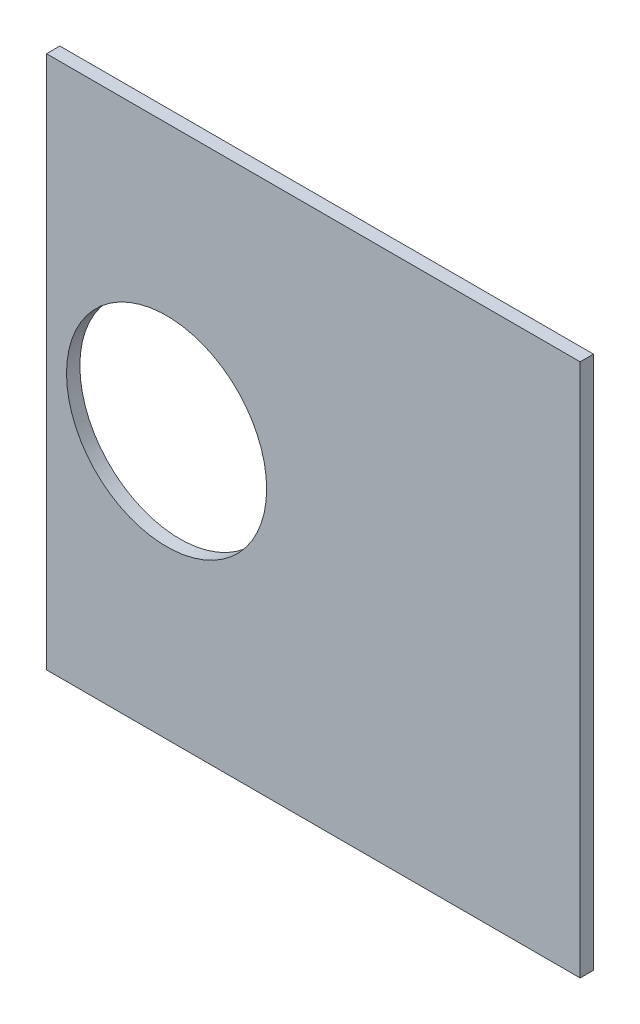
SolidWorks part; units mm, degrees
ref_plane "前视基准面" through (0, 0, 0) normal (0, 0, 1) x (1, 0, 0)
ref_plane "上视基准面" through (0, 0, 0) normal (0, 1, 0) x (1, 0, 0)
ref_plane "右视基准面" through (0, 0, 0) normal (1, 0, 0) x (0, 0, -1)
other "Configuration Table"
sketch "草图1" plane through (0, 0, 0) normal (0, 0, 1) x (1, 0, 0)
  line L1 (-200, -200) -> (200, -200)
  line L2 (-200, -200) -> (-200, 200)
  line L3 (-200, 200) -> (200, 200)
  line L4 (200, -200) -> (200, 200)
  line L5 (-200, -200) -> (200, 200) construction
  line L6 (-200, 200) -> (200, -200) construction
  point P0 (0, 0)
  dimension "D1" = 400
extrude "凸台-拉伸1" add sketch "草图1" along normal blind 10
sketch "草图2" plane through (0, 0, 10) normal (0, 0, 1) x (1, 0, 0)
  circle A1 centre (-110, 0) radius 75
  point P2 (-110.3239, 0)
  dimension "D1" = 150
  dimension "D2" = 110
extrude "切除-拉伸1" cut sketch "草图2" against normal through all
